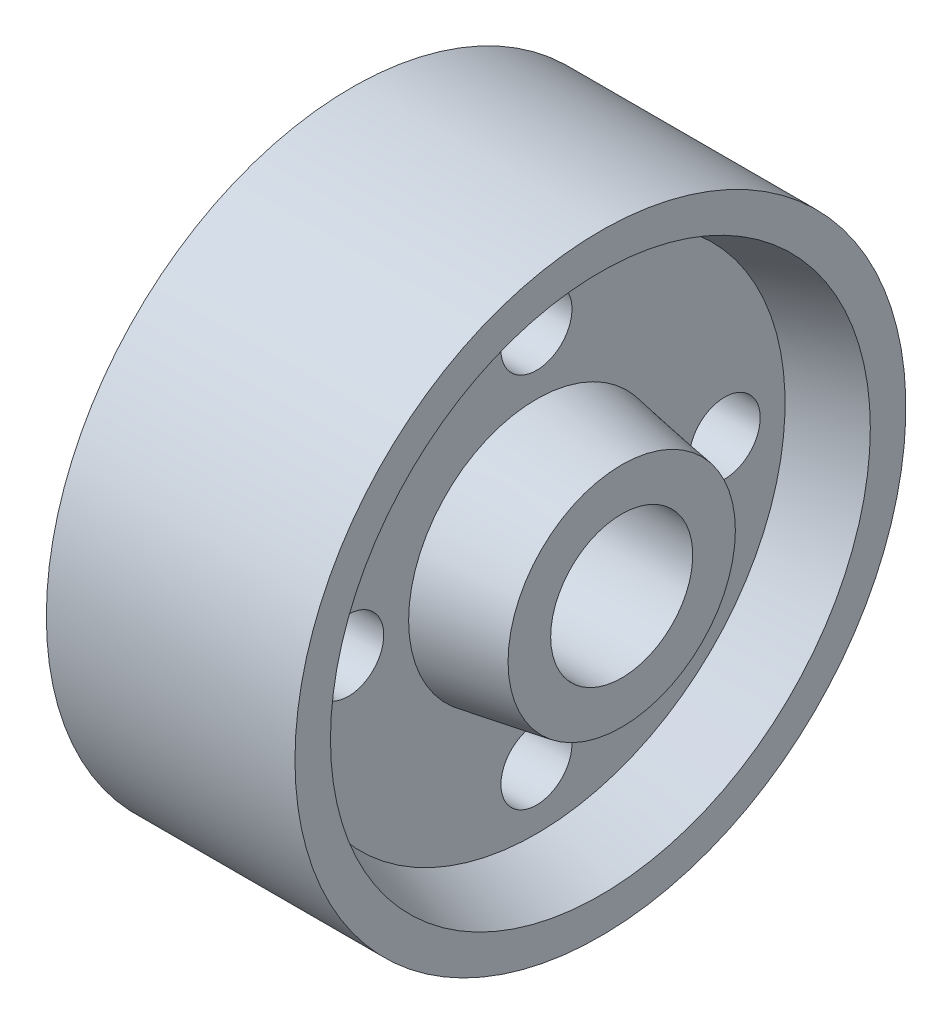
SolidWorks part; units mm, degrees
ref_plane "Front Plane" through (0, 0, 0) normal (0, 0, 1) x (1, 0, 0)
ref_plane "Top Plane" through (0, 0, 0) normal (0, 1, 0) x (1, 0, 0)
ref_plane "Right Plane" through (0, 0, 0) normal (1, 0, 0) x (0, 0, -1)
sketch "Sketch1" plane through (0, 0, 0) normal (0, 1, 0) x (1, 0, 0)
  line L0 (0, 0) -> (86.9592, 0) construction
  line L1 (0, 0) -> (0, 16)
  line L2 (0, 16) -> (12, 18)
  line L3 (12, 18) -> (12, 35)
  line L4 (12, 35) -> (3, 38)
  line L5 (3, 38) -> (3, 43)
  line L6 (3, 43) -> (38, 43)
  line L7 (20.5, 43) -> (20.5, 0) construction
  line L8 (41, 0) -> (41, 16)
  line L9 (41, 16) -> (29, 18)
  line L10 (29, 18) -> (29, 35)
  line L11 (29, 35) -> (38, 38)
  line L12 (38, 38) -> (38, 43)
  line L13 (0, 0) -> (41, 0)
  dimension "D1" = 32
  dimension "D2" = 36
  dimension "D3" = 70
  dimension "D4" = 76
  dimension "D5" = 86
  dimension "D6" = 20.5
  dimension "D7" = 17.5
  dimension "D8" = 12
revolve "Revolve1" add sketch "Sketch1" angle 360 about L0
sketch "Sketch2" plane through (0, 0, 0) normal (-1, 0, 0) x (0, 0, 1)
  circle A0 centre (0, 0) radius 26.5 construction
  circle A1 centre (0, 26.5) radius 5
  circle A2 centre (26.5, 0) radius 5
  circle A3 centre (0, -26.5) radius 5
  circle A4 centre (-26.5, 0) radius 5
  point P14 (0, 0)
  dimension "D1" = 53
  dimension "D2" = 10
  dimension "D3" = 4
extrude "Cut-Extrude1" cut sketch "Sketch2" against normal through all
sketch "Sketch3" plane through (0, 0, 0) normal (-1, 0, 0) x (0, 0, 1)
  circle A0 centre (0, 0) radius 10
  dimension "D1" = 20
extrude "Cut-Extrude2" cut sketch "Sketch3" against normal through all
